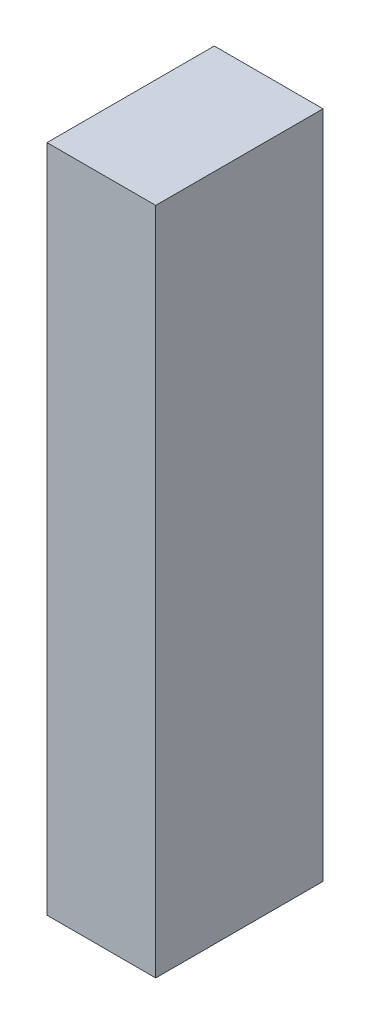
SolidWorks part; units mm, degrees
ref_plane "Front Plane" through (0, 0, 0) normal (0, 0, 1) x (1, 0, 0)
ref_plane "Top Plane" through (0, 0, 0) normal (0, 1, 0) x (1, 0, 0)
ref_plane "Right Plane" through (0, 0, 0) normal (1, 0, 0) x (0, 0, -1)
sketch "Sketch1" plane through (0, 0, 0) normal (0, 1, 0) x (1, 0, 0)
  line L1 (-32.5, 50) -> (32.5, 50)
  line L2 (-32.5, 50) -> (-32.5, -50)
  line L3 (-32.5, -50) -> (32.5, -50)
  line L4 (32.5, 50) -> (32.5, -50)
  line L5 (-32.5, 50) -> (32.5, -50) construction
  line L6 (-32.5, -50) -> (32.5, 50) construction
  point P0 (0, 0)
  dimension "D1" = 65
  dimension "D2" = 100
extrude "Boss-Extrude1" add sketch "Sketch1" along normal blind 400
